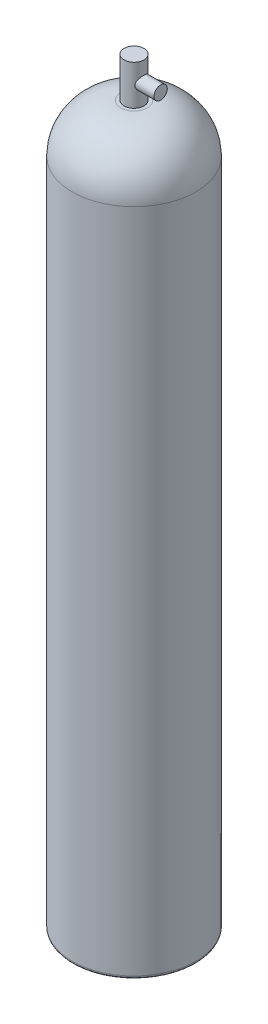
SolidWorks part; units mm, degrees
ref_plane "Front Plane" through (0, 0, 0) normal (0, 0, 1) x (1, 0, 0)
ref_plane "Top Plane" through (0, 0, 0) normal (0, 1, 0) x (1, 0, 0)
ref_plane "Right Plane" through (0, 0, 0) normal (1, 0, 0) x (0, 0, -1)
sketch "Sketch1" plane through (0, 0, 0) normal (0, 0, 1) x (1, 0, 0)
  line L0 (0, -1371.6) -> (111.76, -1371.6)
  line L1 (118.11, -1365.25) -> (118.11, -92.71)
  line L2 (0, -1358.9) -> (105.41, -1358.9)
  line L3 (105.41, -1358.9) -> (105.41, -92.71)
  line L4 (25.4, 0) -> (0, 0)
  line L6 (0, -1358.9) -> (0, -1371.6)
  line L7 (0, 0) -> (0, -12.7)
  line L8 (0, -12.7) -> (25.4, -12.7)
  line L9 (0, -1371.6) -> (0, 0) construction
  arc A0 (118.11, -92.71) -> (25.4, 0) centre (25.4, -92.71) ccw
  arc A1 (111.76, -1371.6) -> (118.11, -1365.25) centre (111.76, -1365.25) ccw
  arc A2 (105.41, -1358.9) -> (105.41, -1358.9) centre (105.41, -1358.9) ccw
  arc A3 (105.41, -92.71) -> (25.4, -12.7) centre (25.4, -92.71) ccw
  dimension "D1" = 6.35
  dimension "D2" = 25.4
  dimension "D3" = 118.11
  dimension "D5" = 1371.6
  dimension "D4" = 12.7
revolve "Revolve1" add sketch "Sketch1" angle 360 about L9
sketch "Sketch2" plane through (0, 0, 0) normal (0, 1, 0) x (1, 0, 0)
  circle A0 centre (0, 0) radius 19.05
  dimension "D1" = 38.1
extrude "Boss-Extrude1" add sketch "Sketch2" along normal blind 76.2
sketch "Sketch3" plane through (0, 0, 0) normal (1, 0, 0) x (0, 0, -1)
  circle A0 centre (0, 38.1) radius 12.7
  dimension "D1" = 25.4
  dimension "D2" = 38.1
extrude "Boss-Extrude2" add sketch "Sketch3" along normal blind 50.8
